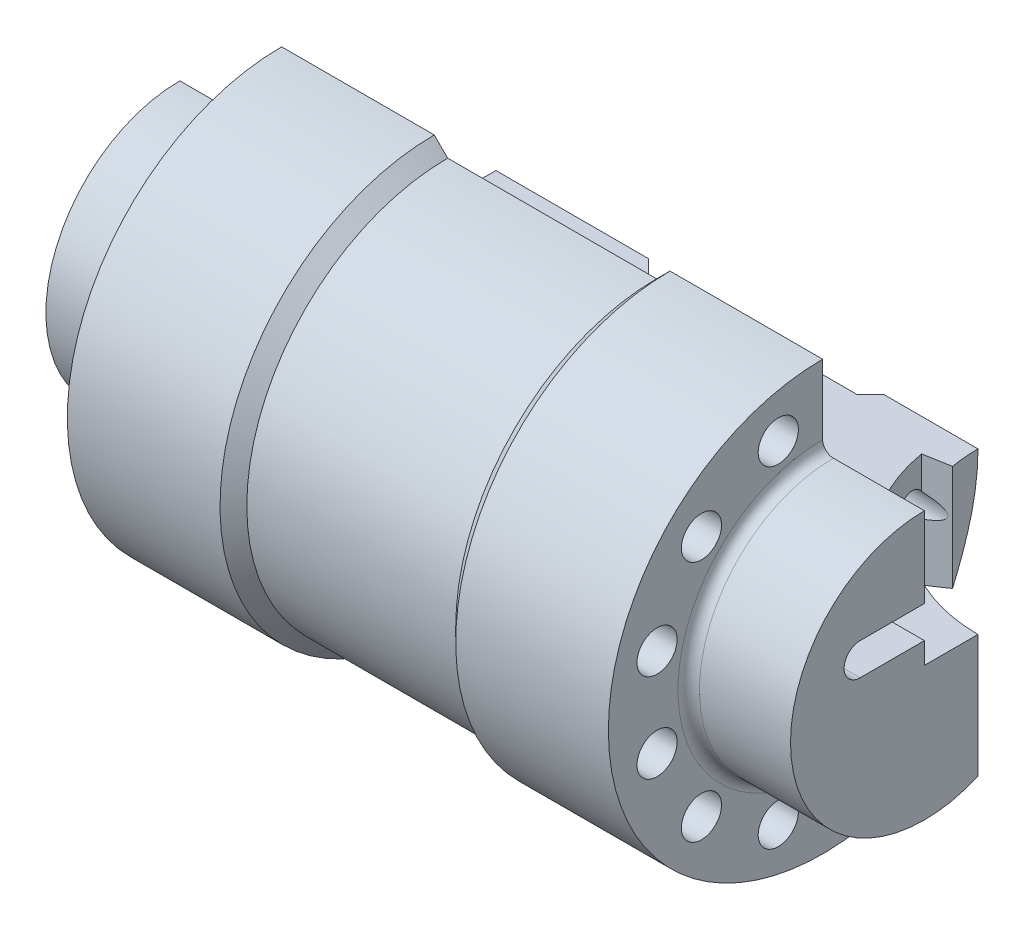
SolidWorks part; units mm, degrees
material "AISI 1020"
ref_plane "Front Plane" through (0, 0, 0) normal (0, 0, 1) x (1, 0, 0)
ref_plane "Top Plane" through (0, 0, 0) normal (0, 1, 0) x (1, 0, 0)
ref_plane "Right Plane" through (0, 0, 0) normal (1, 0, 0) x (0, 0, -1)
sketch "Sketch1" plane through (0, 0, 0) normal (0, 0, 1) x (1, 0, 0)
  line L0 (47.5, 40) -> (50, 37.5)
  line L1 (0, 0) -> (139, 0)
  line L2 (0, 0) -> (0, 25)
  line L3 (19, 40) -> (47.5, 40)
  line L4 (139, 0) -> (139, 25)
  line L7 (0, 25) -> (17, 25)
  line L8 (19, 40) -> (19, 27)
  line L11 (139, 25) -> (122, 25)
  line L12 (120, 40) -> (120, 27)
  line L15 (50, 37.5) -> (89, 37.5)
  line L17 (91.5, 40) -> (89, 37.5)
  line L18 (91.5, 40) -> (120, 40)
  arc A0 (17, 25) -> (19, 27) centre (17, 27) ccw
  arc A1 (122, 25) -> (120, 27) centre (122, 27) cw
  dimension "D9" = 2
  dimension "D10" = 2
  dimension "D1" = 19
  dimension "D2" = 19
  dimension "D3" = 139
  dimension "D4" = 28.5
  dimension "D5" = 28.5
  dimension "D6" = 2.5
  dimension "D7" = 45
  dimension "D8" = 45
  dimension "D11" = 25
  dimension "D12" = 25
  dimension "D13" = 15
revolve "Revolve1" add sketch "Sketch1" angle 270 about L1
sketch "Sketch2" plane through (0, 0, 0) normal (-1, 0, 0) x (0, 0, 1)
  line L0 (0, 7) -> (12, 7) construction
  line L1 (0, 25) -> (0, 0) construction
  line L2 (0, 10) -> (12, 10)
  line L3 (0, 4) -> (12, 4)
  arc A0 (0, 10) -> (0, 4) centre (0, 7) ccw
  arc A1 (12, 4) -> (12, 10) centre (12, 7) ccw
  point P4 (6, 7)
  dimension "D3" = 3
  dimension "D1" = 7
  dimension "D2" = 12
extrude "Cut-Extrude1" cut sketch "Sketch2" against normal through all
sketch "Sketch3" plane through (120, 0, 0) normal (1, 0, 0) x (0, 0, -1)
  line L0 (0, 0) -> (-10.3528, 38.637) construction
  line L1 (0, 27) -> (0, 40) construction
  arc A0 (-4.6093, 31.6663) -> (31.6663, -4.6093) centre (0, 0) ccw
  arc A1 (0, 40) -> (40, 0) centre (0, 0) ccw construction
  circle A2 centre (-8.2822, 30.9096) radius 3.75
  circle A6 centre (30.9096, -8.2822) radius 3.75
  circle A7 centre (22.6274, -22.6274) radius 3.75
  circle A8 centre (8.2822, -30.9096) radius 3.75
  circle A9 centre (-8.2822, -30.9096) radius 3.75
  circle A10 centre (-22.6274, -22.6274) radius 3.75
  circle A11 centre (-30.9096, -8.2822) radius 3.75
  circle A12 centre (-30.9096, 8.2822) radius 3.75
  circle A13 centre (-22.6274, 22.6274) radius 3.75
  arc A14 (4.6093, 31.6663) -> (11.8413, 29.7285) centre (8.2822, 30.9096) ccw [skipped]
  arc A15 (25.1191, 19.825) -> (19.825, 25.1191) centre (22.6274, 22.6274) ccw [skipped]
  arc A16 (29.7285, 11.8413) -> (31.6663, 4.6093) centre (30.9096, 8.2822) ccw [skipped]
  point P35 (0, 0)
  dimension "D1" = 64
  dimension "D3" = 7.5
  dimension "D2" = 15
  dimension "D4" = 12
extrude "Cut-Extrude2" cut sketch "Sketch3" against normal through all contours A2 | A13 | A12 | A11 | A10 | A9 | A8 | A7 | A6
sketch "Sketch5" plane through (0, 0, 0) normal (0, 1, 0) x (1, 0, 0)
  line L1 (139, 25) -> (120, 25) construction
  line L2 (139, 25) -> (139, 40) construction
  line L3 (139, 40) -> (120, 40) construction
  line L4 (120, 25) -> (120, 40) construction
  circle A1 centre (139, 40) radius 30
  dimension "D2" = 60
extrude "Cut-Extrude3" cut sketch "Sketch5" against normal through all
sketch "Sketch6" plane through (0, 0, 0) normal (0, 1, 0) x (1, 0, 0)
  line L5 (104.5317, 33.9223) -> (109.4558, 34.7906)
  line L6 (126.3215, 12.8108) -> (124.2084, 8.2792)
  arc A0 (109, 40) -> (139, 10) centre (139, 40) ccw construction
  arc A1 (104.5317, 33.9223) -> (124.2084, 8.2792) centre (139, 40) ccw
  arc A2 (109.4558, 34.7906) -> (126.3215, 12.8108) centre (139, 40) ccw
  dimension "D1" = 70
extrude "Cut-Extrude4" cut sketch "Sketch6" against normal through all
equation "\"A\"= 139.00"
equation "\"B\"= 19.00"
equation "\"C\"= 28.50"
